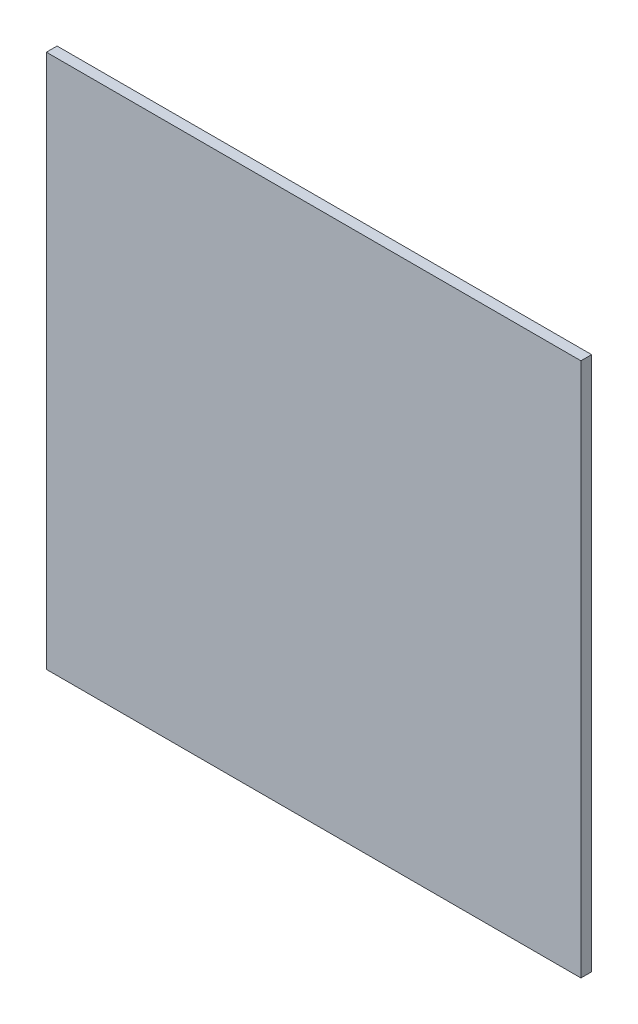
SolidWorks part; units mm, degrees
ref_plane "前视基准面" through (0, 0, 0) normal (0, 0, 1) x (1, 0, 0)
ref_plane "上视基准面" through (0, 0, 0) normal (0, 1, 0) x (1, 0, 0)
ref_plane "右视基准面" through (0, 0, 0) normal (1, 0, 0) x (0, 0, -1)
sketch "草图1" plane through (0, 0, 0) normal (0, 0, 1) x (1, 0, 0)
  line L1 (0, 0) -> (250, 0)
  line L2 (0, 0) -> (0, 250)
  line L3 (0, 250) -> (250, 250)
  line L4 (250, 0) -> (250, 250)
  point P5 (0, 0)
extrude "凸台-拉伸1" add sketch "草图1" along normal blind 5
